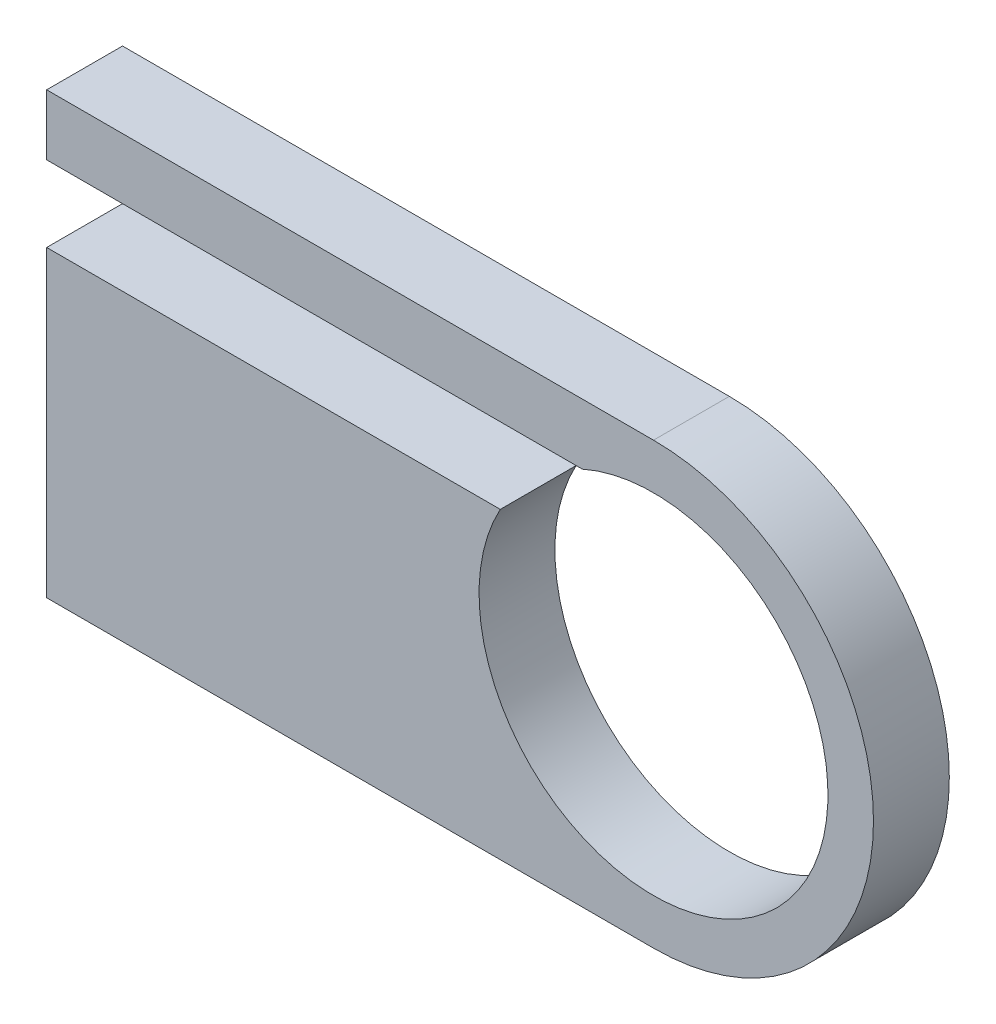
SolidWorks part; units mm, degrees
ref_plane "Front Plane" through (0, 0, 0) normal (0, 0, 1) x (1, 0, 0)
ref_plane "Top Plane" through (0, 0, 0) normal (0, 1, 0) x (1, 0, 0)
ref_plane "Right Plane" through (0, 0, 0) normal (1, 0, 0) x (0, 0, -1)
sketch "Sketch1" plane through (0, 0, 0) normal (0, 0, 1) x (1, 0, 0)
  line L0 (0, 0) -> (0, 4)
  line L2 (0, 0) -> (35.3096, 0)
  line L4 (29.9005, -5) -> (0, -5)
  line L5 (0, -5) -> (0, -25)
  line L6 (0, -25) -> (40, -25)
  line L9 (0, 4) -> (40, 4)
  arc A1 (40, 4) -> (40, -25) centre (40, -10.5) cw
  arc A4 (35.3096, 0) -> (29.9005, -5) centre (40, -10.5) cw
  point P3 (82.6848, 0.6535)
  point P11 (0, 0)
  point P12 (34.4523, -3.4021)
  point P13 (102.6839, -12.2652)
  point P14 (102.6839, -12.2652)
  point P15 (88.7698, -6.6607)
  point P16 (0, 0)
  dimension "D1" = 3
  dimension "D2" = 40
  dimension "D3" = 4
  dimension "D4" = 5
  dimension "D5" = 20
extrude "Boss-Extrude1" add sketch "Sketch1" along normal blind 5
